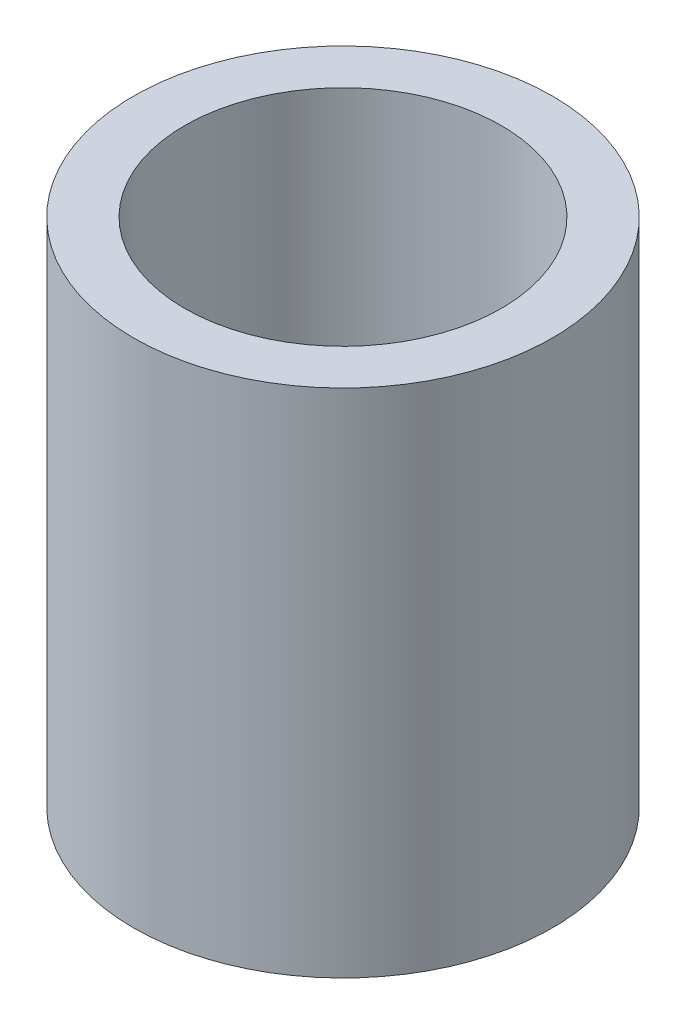
SolidWorks part; units mm, degrees
ref_plane "Front Plane" through (0, 0, 0) normal (0, 0, 1) x (1, 0, 0)
ref_plane "Top Plane" through (0, 0, 0) normal (0, 1, 0) x (1, 0, 0)
ref_plane "Right Plane" through (0, 0, 0) normal (1, 0, 0) x (0, 0, -1)
sketch "Sketch1" plane through (0, 0, 0) normal (0, 1, 0) x (1, 0, 0)
  circle A0 centre (0, 0) radius 1.55
  circle A1 centre (0, 0) radius 2.05
  dimension "D1" = 3.1
  dimension "D2" = 0.5
extrude "Boss-Extrude1" add sketch "Sketch1" along normal blind 5
